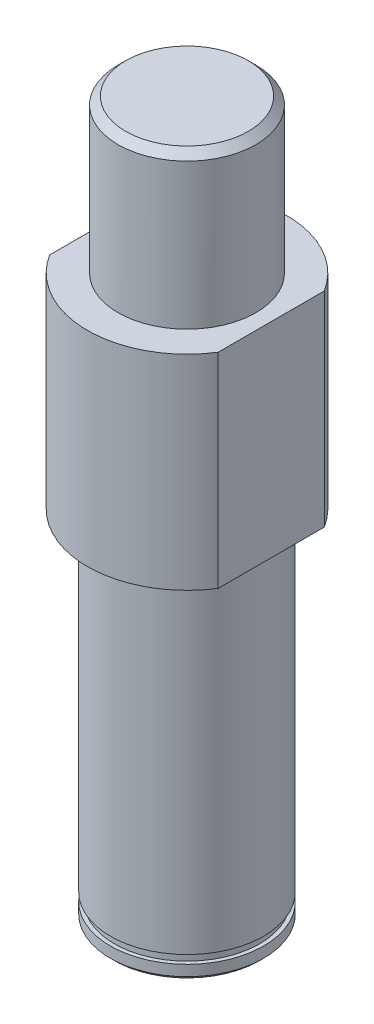
SolidWorks part; units mm, degrees
material "45"
ref_plane "前视基准面" through (0, 0, 0) normal (0, 0, 1) x (1, 0, 0)
ref_plane "上视基准面" through (0, 0, 0) normal (0, 1, 0) x (1, 0, 0)
ref_plane "右视基准面" through (0, 0, 0) normal (1, 0, 0) x (0, 0, -1)
sketch "草图1" plane through (0, 0, 0) normal (0, 0, 1) x (1, 0, 0)
  line L0 (0, 0) -> (0, 292.6233) construction
  line L1 (0, 0) -> (10, 0)
  line L2 (10, 0) -> (10, 1.9)
  line L3 (9, 93) -> (0, 93)
  line L4 (10, 3) -> (10, 63)
  line L5 (10, 1.9) -> (9.5, 1.9)
  line L6 (0, 0) -> (0, 93)
  line L7 (10, 3) -> (9.5, 3)
  line L8 (9.5, 1.9) -> (9.5, 3)
  line L9 (9, 73) -> (13, 73)
  line L10 (13, 73) -> (13, 63)
  line L11 (13, 63) -> (10, 63)
  line L12 (9, 73) -> (9, 93)
  dimension "D1" = 20
  dimension "D2" = 10
  dimension "D3" = 9
  dimension "D4" = 1.9
  dimension "D5" = 1.1
  dimension "D6" = 9.5
  dimension "D7" = 10
  dimension "D8" = 13
  dimension "D9" = 63
revolve "旋转1" add sketch "草图1" angle 360 about L0
cosmetic thread "装饰螺纹线1" parameters "D2"=15.294
chamfer "倒角1" distance 1 angle 45 1 edges at (0, 93, -9)
sketch "草图2" plane through (0, 73, 0) normal (0, 1, 0) x (1, 0, 0)
  line L0 (-11, 6.9282) -> (-11, -6.9282)
  line L1 (11, 6.9282) -> (11, -6.9282)
  circle A0 centre (0, 0) radius 13
  circle M2 centre (0, 0) radius 13
  dimension "D3" = 26
  dimension "D1" = 22
  dimension "D2" = 11
extrude "切除-拉伸1" cut sketch "草图2" against normal through all contours L0 M2 | L1 M2
sketch "草图6" plane through (0, 63, 0) normal (0, -1, 0) x (1, 0, 0)
  line L4 (11, -6.9282) -> (11, 6.9282)
  line L5 (-11, 6.9282) -> (-11, -6.9282)
  line L6 (11, -6.9282) -> (11, 6.9282)
  line L7 (-11, 6.9282) -> (-11, -6.9282)
  arc A4 (11, 6.9282) -> (-11, 6.9282) centre (0, 0) ccw
  arc A5 (-11, -6.9282) -> (11, -6.9282) centre (0, 0) ccw
  arc A6 (11, 6.9282) -> (-11, 6.9282) centre (0, 0) ccw
  arc A7 (-11, -6.9282) -> (11, -6.9282) centre (0, 0) ccw
  dimension "D1" = 0
extrude "凸台-拉伸2" add sketch "草图6" along normal blind 16.7
hole_wizard "M10 螺纹孔1" positions "草图7" profile "草图8" tap size "M10" standard "GB"
sketch "草图7" plane through (0, 0, 0) normal (0, -1, 0) x (-1, 0, 0)
  point P0 (0, 0)
sketch "草图8" plane through (0, 0, 0) normal (1, 0, 0) x (0, 0, -1)
  line L0 (0, 0) -> (0, 30.0537)
  line L1 (0, 30.0537) -> (4.25, 27.5)
  line L2 (4.25, 27.5) -> (4.25, 0)
  line L5 (4.25, 0) -> (0, 0)
  line L10 (0, 30.0537) -> (-4.25, 27.5) construction
  line L11 (0, -6.35) -> (0, 107.95) construction
  dimension "螺纹孔钻头直径" = 8.5
  dimension "螺纹孔钻头深度" = 27.5
  dimension "导头角度" = 118
cosmetic thread "孔螺蚊线2" parameters "D1"=20, "D2"=10
chamfer "倒角2" distance 0.5 angle 45 1 edges at (0, 0, -10)
